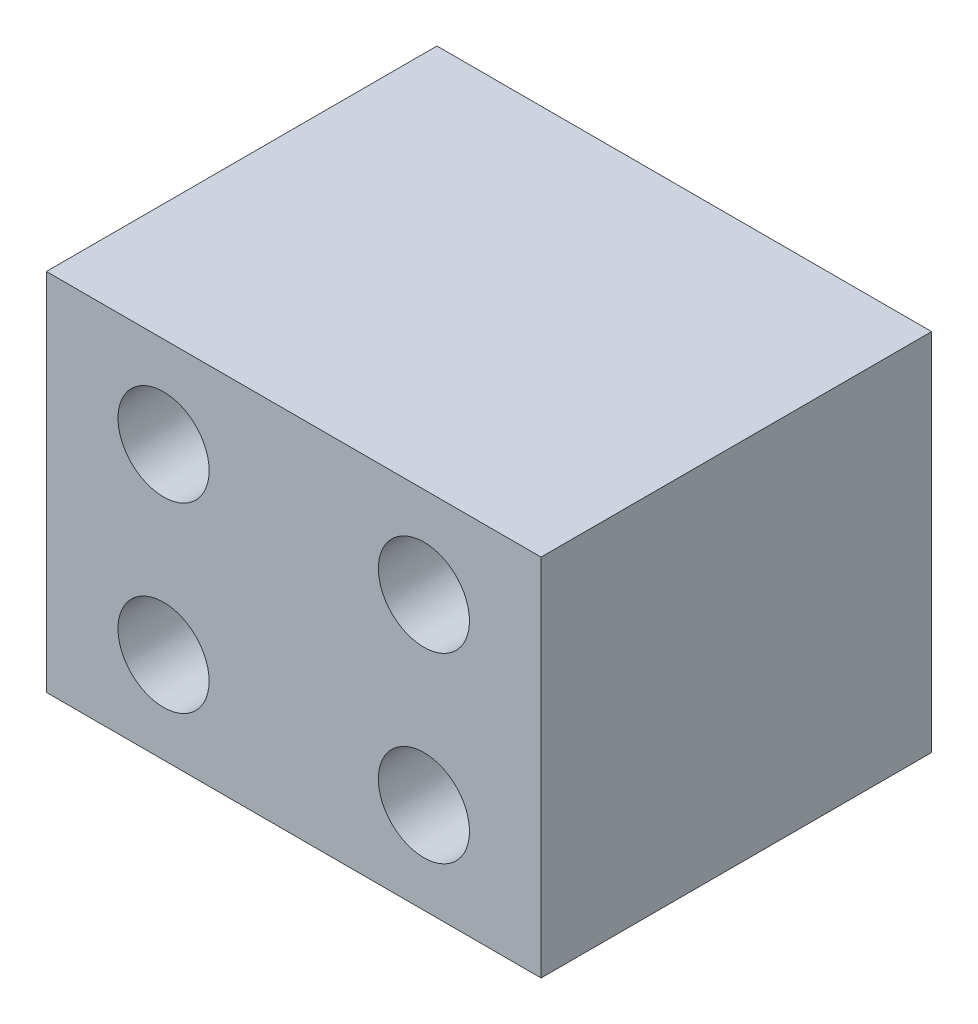
SolidWorks part; units mm, degrees
material "ABS"
ref_plane "前视基准面" through (0, 0, 0) normal (0, 0, 1) x (1, 0, 0)
ref_plane "上视基准面" through (0, 0, 0) normal (0, 1, 0) x (1, 0, 0)
ref_plane "右视基准面" through (0, 0, 0) normal (1, 0, 0) x (0, 0, -1)
sketch "草图1" plane through (0, 0, 0) normal (0, 0, 1) x (1, 0, 0)
  line L1 (-9.5, -7) -> (9.5, -7)
  line L2 (-9.5, -7) -> (-9.5, 7)
  line L3 (-9.5, 7) -> (9.5, 7)
  line L4 (9.5, -7) -> (9.5, 7)
  line L5 (-9.5, -7) -> (9.5, 7) construction
  line L6 (-9.5, 7) -> (9.5, -7) construction
  line L7 (-5, -3.5) -> (5, -3.5) construction
  line L8 (-5, -3.5) -> (-5, 3.5) construction
  line L9 (-5, 3.5) -> (5, 3.5) construction
  line L10 (5, -3.5) -> (5, 3.5) construction
  line L11 (-5, -3.5) -> (5, 3.5) construction
  line L12 (-5, 3.5) -> (5, -3.5) construction
  circle A0 centre (-5, 3.5) radius 1.75
  circle A1 centre (5, 3.5) radius 1.75
  circle A2 centre (5, -3.5) radius 1.75
  circle A3 centre (-5, -3.5) radius 1.75
  point P0 (0, 0)
  point P6 (0, 0)
  dimension "D5" = 3.5
  dimension "D1" = 10
  dimension "D2" = 7
  dimension "D3" = 14
  dimension "D4" = 19
extrude "凸台-拉伸1" add sketch "草图1" along normal blind 15
